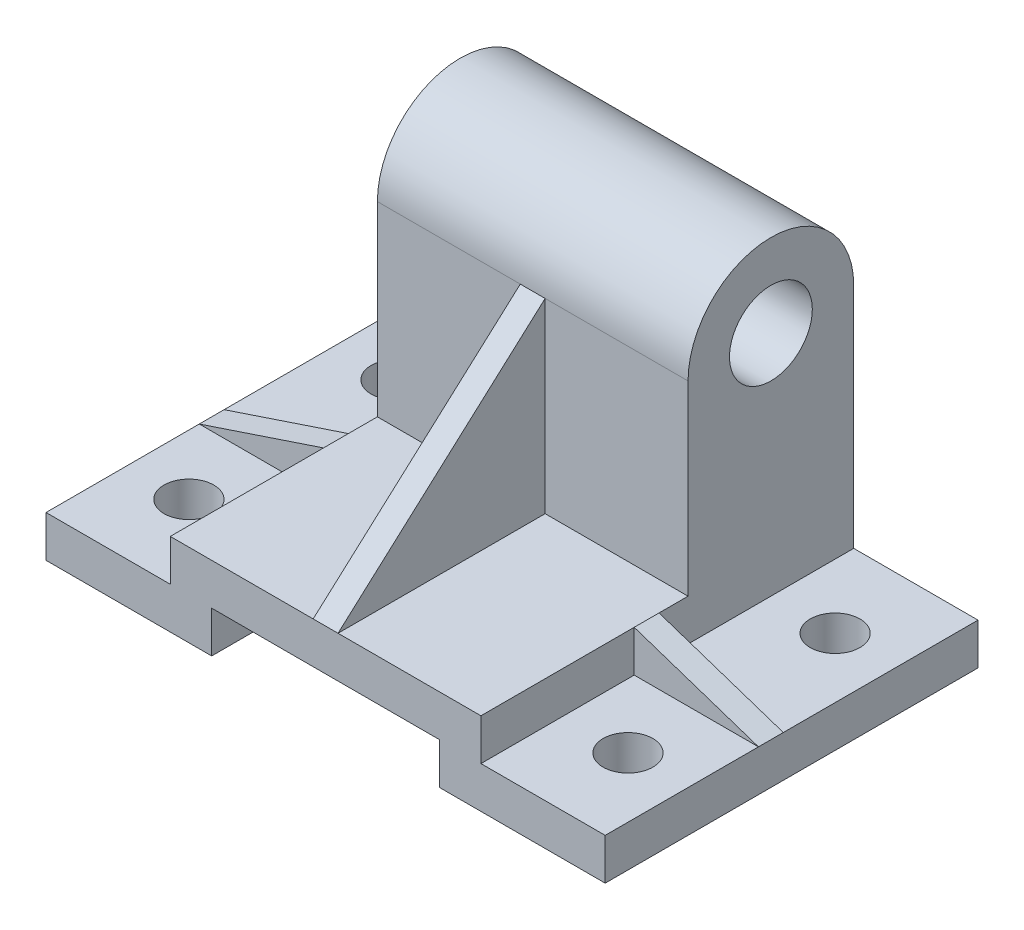
SolidWorks part; units mm, degrees
material "1023 Carbon Steel Sheet (SS)"
ref_plane "Front Plane" through (0, 0, 0) normal (0, 0, 1) x (1, 0, 0)
ref_plane "Top Plane" through (0, 0, 0) normal (0, 1, 0) x (1, 0, 0)
ref_plane "Right Plane" through (0, 0, 0) normal (1, 0, 0) x (0, 0, -1)
sketch "Sketch1" plane through (0, 0, 0) normal (0, 0, 1) x (1, 0, 0)
  line L0 (0, 0) -> (27.5, 0)
  line L1 (27.5, 0) -> (27.5, -10)
  line L14 (27.5, -10) -> (67.5, -10)
  line L15 (67.5, -10) -> (67.5, 0)
  line L16 (67.5, 0) -> (37.5, 0)
  line L17 (37.5, 0) -> (37.5, 10)
  line L18 (37.5, 10) -> (-37.5, 10)
  line L19 (-37.5, 10) -> (-37.5, 0)
  line L20 (-37.5, 0) -> (-67.5, 0)
  line L21 (-67.5, 0) -> (-67.5, -10)
  line L22 (-67.5, -10) -> (-27.5, -10)
  line L23 (-27.5, -10) -> (-27.5, 0)
  line L24 (-27.5, 0) -> (0, 0)
  point P2 (0, 0)
  point P11 (0, 0)
  point P15 (0, 0)
  point P16 (0, 10)
  point P17 (0, 0)
  point P19 (0, 0)
  point P20 (0, 0)
  point P21 (0, 0)
  point P22 (-27.5, -5)
  point P23 (0, 0)
  point P24 (0, 0)
  dimension "D1" = 55
  dimension "D2" = 135
  dimension "D3" = 75
  dimension "D4" = 10
  dimension "D5" = 10
  dimension "D6" = 10
  dimension "D7" = 10
extrude "Boss-Extrude1" add sketch "Sketch1" along normal mid plane 90
ref_plane "Plane1" through (0, 0, 5) normal (0, 0, 1) x (1, 0, 0)
sketch "Sketch3" plane through (0, 0, 5) normal (0, 0, 1) x (1, 0, 0)
  line L3 (37.5, 10) -> (67.5, 0)
  point P1 (0, 0)
  point P2 (0, 0)
rib "Rib1" sketch "Sketch3" sketch "Sketch3" thickness 6 extrusion direction parallel to sketch draft on no parameters "D1"=6
mirror "Mirror1" about plane through (0, 0, 0) normal (1, 0, 0) of "Rib1"
sketch "Sketch5" plane through (0, 0, 0) normal (0, 1, 0) x (1, 0, 0)
  line L0 (67.5, -45) -> (37.5, -45) construction
  circle A0 centre (53, -25) radius 6
  dimension "D1" = 12
  dimension "D2" = 20
  dimension "D3" = 53
extrude "Cut-Extrude1" cut sketch "Sketch5" against normal blind 90
mirror "Mirror2" about plane through (0, 0, 0) normal (1, 0, 0) of "Cut-Extrude1"
sketch "Sketch6" plane through (0, 0, 0) normal (0, 1, 0) x (1, 0, 0)
  circle A0 centre (53, 25) radius 6
  dimension "D1" = 12
  dimension "D2" = 20
  dimension "D3" = 53
extrude "Cut-Extrude2" cut sketch "Sketch6" against normal blind 90
mirror "Mirror3" about plane through (0, 0, 0) normal (1, 0, 0) of "Cut-Extrude2"
sketch "Sketch7" plane through (0, 0, 0) normal (1, 0, 0) x (0, 0, -1)
  line L0 (-2, 10) -> (45, 10) construction
  line L1 (5, 10) -> (45, 10)
  line L2 (45, 10) -> (45, 55)
  line L3 (5, 55) -> (5, 10)
  circle A0 centre (25, 55) radius 10
  arc A1 (45, 55) -> (5, 55) centre (25, 55) ccw
  dimension "D1" = 40
  dimension "D2" = 20
  dimension "D3" = 45
extrude "Boss-Extrude2" add sketch "Sketch7" along normal mid plane 75
sketch "Sketch8" plane through (0, 0, 0) normal (1, 0, 0) x (0, 0, -1)
  line L0 (5, 55) -> (-45, 10)
  point P3 (0, 0)
rib "Rib2" sketch "Sketch8" sketch "Sketch8" thickness 6 extrusion direction parallel to sketch draft on no parameters "D1"=6
